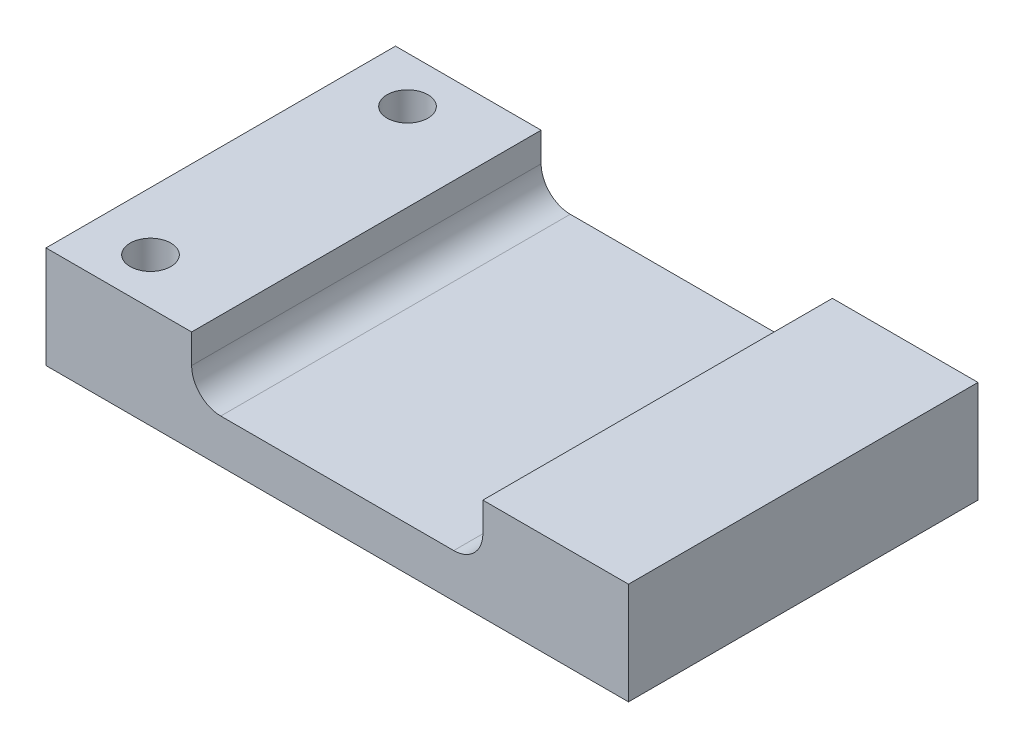
SolidWorks part; units mm, degrees
ref_plane "Front Plane" through (0, 0, 0) normal (0, 0, 1) x (1, 0, 0)
ref_plane "Top Plane" through (0, 0, 0) normal (0, 1, 0) x (1, 0, 0)
ref_plane "Right Plane" through (0, 0, 0) normal (1, 0, 0) x (0, 0, -1)
sketch "Sketch1" plane through (0, 0, 0) normal (0, 1, 0) x (1, 0, 0)
  line L0 (0, 0) -> (0, 12) construction
  line L1 (-20, 12) -> (20, 12)
  line L2 (-20, 12) -> (-20, -12)
  line L3 (-20, -12) -> (20, -12)
  line L4 (20, 12) -> (20, -12)
  line L5 (0, 0) -> (20, 0) construction
  line L6 (-16, 12) -> (-16, -12) construction
  circle A0 centre (-16, 8.825) radius 1.4
  circle A1 centre (-16, -8.825) radius 1.4
  point P14 (0, 0)
  dimension "D1" = 2.8
  dimension "D2" = 17.65
  dimension "D3" = 40
  dimension "D4" = 24
  dimension "D5" = 4
extrude "Boss-Extrude1" add sketch "Sketch1" along normal blind 7
sketch "Sketch2" plane through (0, 7, 0) normal (0, 1, 0) x (1, 0, 0)
  line L0 (-10, 12) -> (10, 12)
  line L1 (20, 12) -> (-20, 12) construction
  line L2 (10, 12) -> (10, -12)
  line L3 (-20, -12) -> (20, -12) construction
  line L4 (10, -12) -> (-10, -12)
  line L5 (-10, -12) -> (-10, 12)
  line L6 (20, -12) -> (20, 12) construction
  circle A0 centre (-16, -8.825) radius 1.4 construction
  dimension "D1" = 6
  dimension "D2" = 10
extrude "Cut-Extrude1" cut sketch "Sketch2" against normal blind 4
fillet "Fillet1" radius 2 2 edges at (10, 3, 0) (-10, 3, 0)
sketch "Sketch3" plane through (0, 0, 0) normal (0, -1, 0) x (1, 0, 0)
  line L0 (-20, 12) -> (20, 12) construction
  line L1 (-14.4989, 6.225) -> (-12.9978, 8.825)
  line L2 (-12.9978, 8.825) -> (-14.4989, 11.425)
  line L3 (-14.4989, 11.425) -> (-17.5011, 11.425)
  line L4 (-17.5011, 11.425) -> (-19.0022, 8.825)
  line L5 (-19.0022, 8.825) -> (-17.5011, 6.225)
  line L6 (-17.5011, 6.225) -> (-14.4989, 6.225)
  line L7 (-14.4989, -11.425) -> (-12.9978, -8.825)
  line L8 (-12.9978, -8.825) -> (-14.4989, -6.225)
  line L9 (-14.4989, -6.225) -> (-17.5011, -6.225)
  line L10 (-17.5011, -6.225) -> (-19.0022, -8.825)
  line L11 (-19.0022, -8.825) -> (-17.5011, -11.425)
  line L12 (-17.5011, -11.425) -> (-14.4989, -11.425)
  circle A0 centre (-16, 8.825) radius 2.6 construction
  circle A1 centre (-16, -8.825) radius 2.6 construction
  dimension "D1" = 5.2
  dimension "D2" = 5.2
extrude "Cut-Extrude2" cut sketch "Sketch3" against normal blind 2.5
